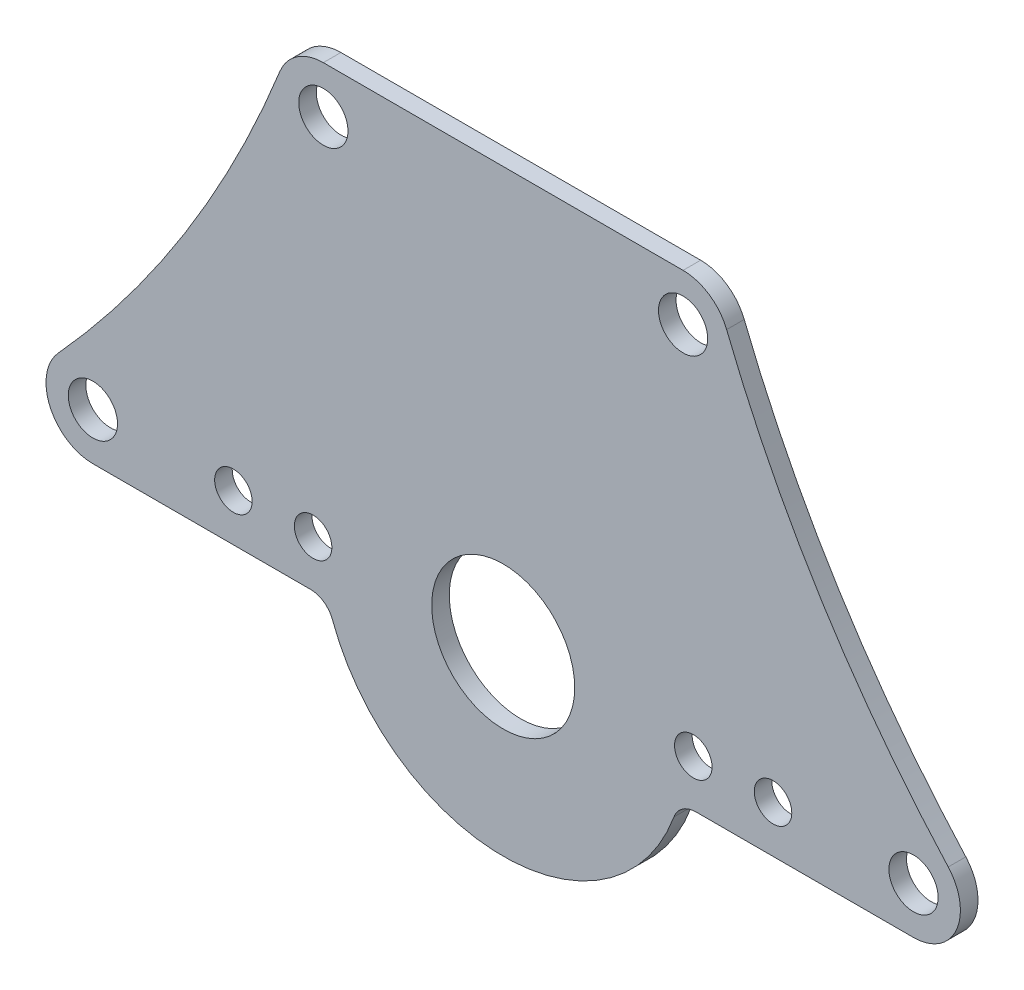
SolidWorks part; units mm, degrees
material "5052-H34"
ref_plane "正面" through (0, 0, 0) normal (0, 0, 1) x (1, 0, 0)
ref_plane "平面" through (0, 0, 0) normal (0, 1, 0) x (1, 0, 0)
ref_plane "右側面" through (0, 0, 0) normal (1, 0, 0) x (0, 0, -1)
sketch "ｽｹｯﾁ1" plane through (0, 0, 0) normal (0, 0, 1) x (1, 0, 0)
  line L0 (0, 5.5) -> (0, 0) construction
  line L1 (-7.5, 5.5) -> (7.5, 5.5) construction
  line L2 (-7.5, 5.5) -> (-7.5, -5.5) construction
  line L3 (-7.5, -5.5) -> (7.5, -5.5) construction
  line L4 (7.5, 5.5) -> (7.5, -5.5) construction
  line L5 (-7.5, 5.5) -> (7.5, -5.5) construction
  line L6 (-7.5, -5.5) -> (7.5, 5.5) construction
  line L7 (0, 0) -> (7.5, 0) construction
  line L8 (0, 0) -> (0, -20) construction
  line L9 (0, -12.5) -> (0, 29.8609) construction
  line L10 (0, -20) -> (35, -20) construction
  line L11 (0, -20) -> (15.343, 11.4578) construction
  line L12 (0, -20) -> (111.9546, 49.957) construction
  line L13 (-35, -24) -> (0, -24)
  line L14 (-15.343, 15.4578) -> (15.343, 15.4578)
  line L15 (0, -24) -> (35, -24)
  circle A0 centre (7.5, 5.5) radius 1.6 construction
  circle A1 centre (-7.5, 5.5) radius 1.6 construction
  circle A2 centre (7.5, -5.5) radius 1.6 construction
  circle A3 centre (-7.5, -5.5) radius 1.6 construction
  circle A4 centre (0, -20) radius 6.1
  circle A5 centre (0, -20) radius 30 construction
  circle A6 centre (0, -20) radius 35 construction
  circle A7 centre (35, -20) radius 2.1
  circle A8 centre (-35, -20) radius 2.1
  circle A9 centre (15.343, 11.4578) radius 2.1
  circle A10 centre (-15.343, 11.4578) radius 2.1
  arc A11 (34.7714, -23.9935) -> (37.9598, -17.3093) centre (35, -20) ccw
  arc A12 (19.0588, 12.9385) -> (14.7529, 15.414) centre (15.343, 11.4578) ccw
  arc A13 (-34.7714, -23.9935) -> (-37.9598, -17.3093) centre (-35, -20) cw
  arc A14 (-19.0588, 12.9385) -> (-14.7529, 15.414) centre (-15.343, 11.4578) cw
  arc A15 (19.0588, 12.9385) -> (37.9598, -17.3093) centre (111.9546, 49.957) ccw
  arc A16 (37.9598, -17.3093) -> (19.0588, 12.9385) centre (111.9546, 49.957) ccw construction
  arc A17 (-19.0588, 12.9385) -> (-37.9598, -17.3093) centre (-111.9546, 49.957) cw
  arc A18 (5.9222, 14.4953) -> (14.7529, 15.414) centre (0, 114.3198) ccw construction
  arc A19 (0, 214.3198) -> (-14.7529, 15.414) centre (0, 114.3198) ccw construction
  arc A20 (94.0358, 148.3385) -> (0, 214.3198) centre (0, 114.3198) ccw construction
  arc A21 (14.7529, 15.414) -> (17.9189, 15.9383) centre (0, 114.3198) ccw construction
  arc A22 (17.9189, 15.9383) -> (94.0358, 148.3385) centre (0, 114.3198) ccw construction
  circle A24 centre (0, -20) radius 15.5
  arc A25 (-14.7529, 15.414) -> (-5.9222, 14.4953) centre (0, 114.3198) ccw construction
  arc A26 (-5.9222, 14.4953) -> (0, 14.3198) centre (0, 114.3198) ccw construction
  arc A27 (0, 14.3198) -> (5.9222, 14.4953) centre (0, 114.3198) ccw construction
  arc A37 (-11.6535, 13.003) -> (-18.8321, 9.5017) centre (-15.343, 11.4578) cw construction
  arc A38 (-18.8321, 9.5017) -> (-19.0588, 12.9385) centre (-15.343, 11.4578) cw construction
  arc A39 (-14.7529, 15.414) -> (-11.6535, 13.003) centre (-15.343, 11.4578) cw construction
  arc A40 (13.5895, 7.8626) -> (18.8321, 9.5017) centre (15.343, 11.4578) ccw construction
  arc A41 (18.8321, 9.5017) -> (19.0588, 12.9385) centre (15.343, 11.4578) ccw construction
  arc A42 (11.6535, 13.003) -> (13.5895, 7.8626) centre (15.343, 11.4578) ccw construction
  arc A43 (14.7529, 15.414) -> (11.6535, 13.003) centre (15.343, 11.4578) ccw construction
  arc A44 (34.7714, -16.0065) -> (31, -20) centre (35, -20) ccw construction
  arc A45 (31, -20) -> (34.7714, -23.9935) centre (35, -20) ccw construction
  arc A46 (37.9598, -17.3093) -> (34.7714, -16.0065) centre (35, -20) ccw construction
  arc A47 (-34.7714, -16.0065) -> (-34.7714, -23.9935) centre (-35, -20) cw construction
  arc A48 (-37.9598, -17.3093) -> (-34.7714, -16.0065) centre (-35, -20) cw construction
  point P0 (0, 0)
  dimension "D3" = 3.2
  dimension "D4" = 12.2
  dimension "D6" = 60
  dimension "D7" = 70
  dimension "D8" = 4.2
  dimension "D10" = 8
  dimension "D12" = 200
  dimension "D13" = 100
  dimension "D14" = 31
  dimension "D1" = 15
  dimension "D2" = 11
  dimension "D5" = 20
  dimension "D9" = 64
extrude "ﾎﾞｽ - 押し出し1" add sketch "ｽｹｯﾁ1" along normal blind 1.5
sketch "ｽｹｯﾁ2" plane through (0, 0, 1.5) normal (0, 0, 1) x (1, 0, 0)
  line L1 (0, -20) -> (0, 3.015) construction
  circle A0 centre (0, -20) radius 6.1 construction
  circle A1 centre (0, -20) radius 6.1
  circle A2 centre (0, -20) radius 23.015 construction
  circle A3 centre (23.015, -20) radius 1.6
  circle A4 centre (-23.015, -20) radius 1.6
  circle A5 centre (0, -20) radius 16.215 construction
  circle A6 centre (16.215, -20) radius 1.6
  circle A7 centre (-16.215, -20) radius 1.6
  dimension "D1" = 46.03
  dimension "D2" = 3.2
  dimension "D3" = 32.43
extrude "ｶｯﾄ - 押し出し1" cut sketch "ｽｹｯﾁ2" against normal through all
fillet "ﾌｨﾚｯﾄ1" radius 2 2 edges at (14.975, -24, 0.75) (-14.975, -24, 0.75)
